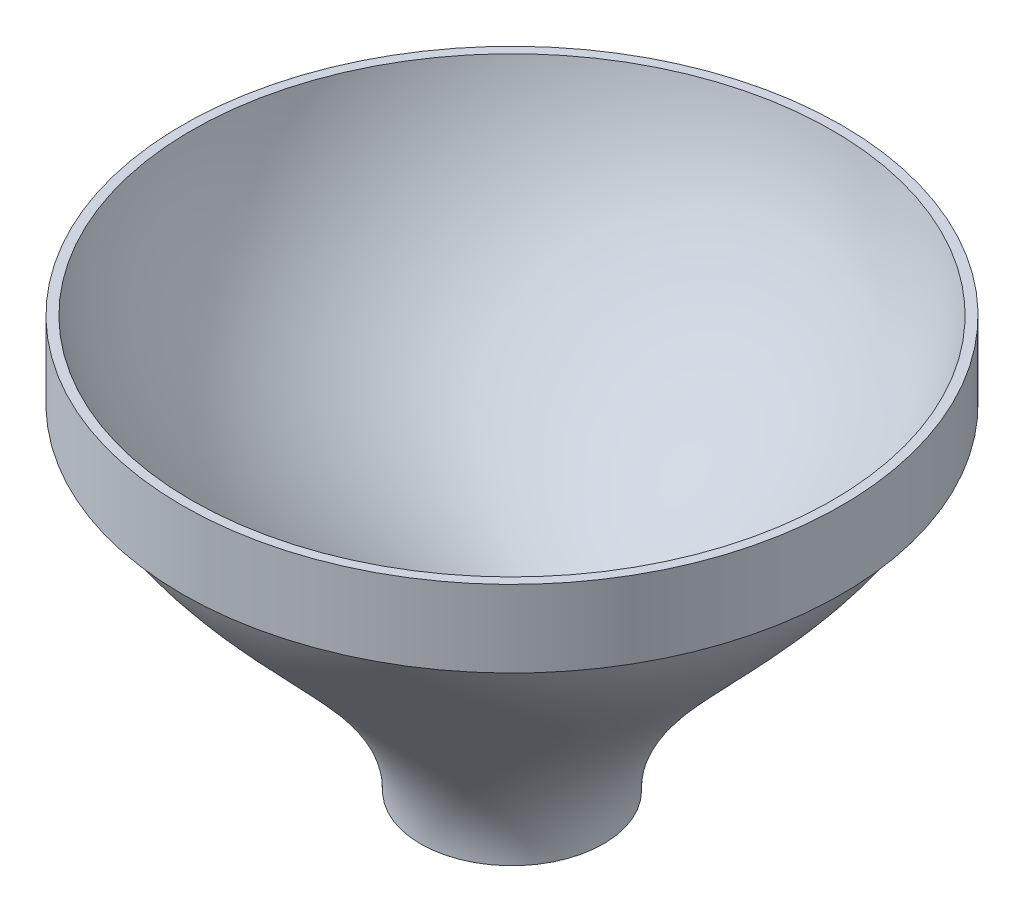
SolidWorks part; units mm, degrees
ref_plane "Płaszczyzna przednia" through (0, 0, 0) normal (0, 0, 1) x (1, 0, 0)
ref_plane "Płaszczyzna górna" through (0, 0, 0) normal (0, 1, 0) x (1, 0, 0)
ref_plane "Płaszczyzna prawa" through (0, 0, 0) normal (1, 0, 0) x (0, 0, -1)
sketch "Sketch1" plane through (0, 0, 0) normal (0, 0, 1) x (1, 0, 0)
  line L15 (24.8342, 148.4714) -> (24.8342, -40.5547) construction
  line L26 (18.8342, 99.8755) -> (16.8342, 99.8755)
  line L30 (-3.1658, 129.1655) -> (-3.9658, 129.1655)
  line L32 (-3.1658, 135.8755) -> (-3.9658, 135.8755)
  line L33 (-3.9658, 135.8755) -> (-3.9658, 129.1655)
  spline S0 degree 3 poles (-3.1658, 135.8755) (0.4907, 117.3938) (18.1254, 113.9802) (18.8342, 99.8755) knots 0 0 0 0 1 1 1 1
  spline S1 degree 3 poles (-3.1658, 129.1655) (1.3725, 118.8356) (17.0932, 110.0443) (16.8342, 99.8755) knots 0 0 0 0 1 1 1 1
  dimension "D7" = 6
  dimension "D1" = 6.71
  dimension "D2" = 0.8
  dimension "D3" = 2
  dimension "D4" = 28
  dimension "D6" = 36
revolve "Revolve1" add sketch "Sketch1" angle 360 about L15
equation "\"outerdiameter\"= 30"
equation "\"wallthick\"= 2"
equation "\"D4@Sketch1\"=\"outerdiameter\"-\"wallthick\""
